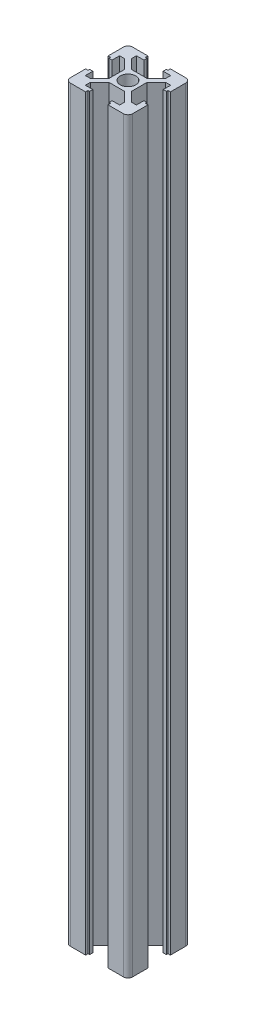
SolidWorks part; units mm, degrees
ref_plane "前视基准面" through (0, 0, 0) normal (0, 0, 1) x (1, 0, 0)
ref_plane "上视基准面" through (0, 0, 0) normal (0, 1, 0) x (1, 0, 0)
ref_plane "右视基准面" through (0, 0, 0) normal (1, 0, 0) x (0, 0, -1)
other "Configuration Table"
sketch "草图1" plane through (0, 0, 0) normal (0, 1, 0) x (1, 0, 0)
  line L0 (-4.4156, 1.3346) -> (-4.4156, 4.4346) construction
  line L1 (-4.4156, 3.874) -> (-4.4156, -1.2047)
  line L2 (1.7237, 4.9346) -> (-3.3549, 4.9346)
  line L3 (2.7844, -1.2047) -> (2.7844, 3.874)
  line L4 (-3.3549, -2.2654) -> (1.7237, -2.2654)
  line L5 (-10.8156, 1.3346) -> (9.1844, 1.3346) construction
  line L6 (-0.8156, 11.3346) -> (-0.8156, -8.6654) construction
  line L7 (-10.8156, 11.3346) -> (-0.8156, 1.3346) construction
  line L8 (-10.8156, 4.9346) -> (-4.4156, 4.9346) construction
  line L9 (-10.0156, 4.4346) -> (-3.9156, 4.4346) construction
  line L10 (-9.0156, 6.8346) -> (-6.3156, 6.8346) construction
  line L11 (-7.3763, 6.8346) -> (-4.4156, 3.874) construction
  line L12 (-10.8156, 9.8346) -> (-10.8156, 4.9346)
  line L13 (-10.8156, 4.9346) -> (-10.0156, 4.9346)
  line L14 (-10.0156, 4.9346) -> (-10.0156, 4.4346)
  line L15 (-10.0156, 4.4346) -> (-9.0156, 4.4346)
  line L16 (-9.0156, 4.4346) -> (-9.0156, 6.8346)
  line L17 (-9.0156, 6.8346) -> (-7.3763, 6.8346)
  line L18 (-7.3763, 6.8346) -> (-4.4156, 3.874)
  line L19 (-3.9156, 10.5346) -> (-3.9156, 9.5346)
  line L20 (-4.4156, 10.5346) -> (-3.9156, 10.5346)
  line L21 (-4.4156, 11.3346) -> (-4.4156, 10.5346)
  line L22 (-9.3156, 11.3346) -> (-4.4156, 11.3346)
  line L23 (-3.9156, 9.5346) -> (-6.3156, 9.5346)
  line L24 (-6.3156, 9.5346) -> (-6.3156, 7.8953)
  line L25 (-6.3156, 7.8953) -> (-3.3549, 4.9346)
  line L26 (9.1844, 11.3346) -> (-0.8156, 1.3346) construction
  line L27 (4.6844, 7.8953) -> (1.7237, 4.9346)
  line L28 (4.6844, 9.5346) -> (4.6844, 7.8953)
  line L29 (2.2844, 9.5346) -> (4.6844, 9.5346)
  line L30 (2.2844, 10.5346) -> (2.2844, 9.5346)
  line L31 (2.7844, 10.5346) -> (2.2844, 10.5346)
  line L32 (2.7844, 11.3346) -> (2.7844, 10.5346)
  line L33 (7.6844, 11.3346) -> (2.7844, 11.3346)
  line L34 (9.1844, 9.8346) -> (9.1844, 4.9346)
  line L35 (9.1844, 4.9346) -> (8.3844, 4.9346)
  line L36 (8.3844, 4.9346) -> (8.3844, 4.4346)
  line L37 (8.3844, 4.4346) -> (7.3844, 4.4346)
  line L38 (7.3844, 4.4346) -> (7.3844, 6.8346)
  line L39 (7.3844, 6.8346) -> (5.7451, 6.8346)
  line L40 (5.7451, 6.8346) -> (2.7844, 3.874)
  line L41 (9.1844, -8.6654) -> (-0.8156, 1.3346) construction
  line L42 (5.7451, -4.1654) -> (2.7844, -1.2047)
  line L43 (7.3844, -4.1654) -> (5.7451, -4.1654)
  line L44 (7.3844, -1.7654) -> (7.3844, -4.1654)
  line L45 (8.3844, -1.7654) -> (7.3844, -1.7654)
  line L46 (8.3844, -2.2654) -> (8.3844, -1.7654)
  line L47 (9.1844, -2.2654) -> (8.3844, -2.2654)
  line L48 (9.1844, -7.1654) -> (9.1844, -2.2654)
  line L49 (7.6844, -8.6654) -> (2.7844, -8.6654)
  line L50 (2.7844, -8.6654) -> (2.7844, -7.8654)
  line L51 (2.7844, -7.8654) -> (2.2844, -7.8654)
  line L52 (2.2844, -7.8654) -> (2.2844, -6.8654)
  line L53 (2.2844, -6.8654) -> (4.6844, -6.8654)
  line L54 (4.6844, -6.8654) -> (4.6844, -5.226)
  line L55 (4.6844, -5.226) -> (1.7237, -2.2654)
  line L56 (-10.8156, -8.6654) -> (-0.8156, 1.3346) construction
  line L57 (-6.3156, -5.226) -> (-3.3549, -2.2654)
  line L58 (-6.3156, -6.8654) -> (-6.3156, -5.226)
  line L59 (-3.9156, -6.8654) -> (-6.3156, -6.8654)
  line L60 (-3.9156, -7.8654) -> (-3.9156, -6.8654)
  line L61 (-4.4156, -7.8654) -> (-3.9156, -7.8654)
  line L62 (-4.4156, -8.6654) -> (-4.4156, -7.8654)
  line L63 (-9.3156, -8.6654) -> (-4.4156, -8.6654)
  line L64 (-10.8156, -7.1654) -> (-10.8156, -2.2654)
  line L65 (-10.8156, -2.2654) -> (-10.0156, -2.2654)
  line L66 (-10.0156, -2.2654) -> (-10.0156, -1.7654)
  line L67 (-10.0156, -1.7654) -> (-9.0156, -1.7654)
  line L68 (-9.0156, -1.7654) -> (-9.0156, -4.1654)
  line L69 (-9.0156, -4.1654) -> (-7.3763, -4.1654)
  line L70 (-7.3763, -4.1654) -> (-4.4156, -1.2047)
  arc A0 (-10.8156, 9.8346) -> (-9.3156, 11.3346) centre (-9.3156, 9.8346) cw
  circle A1 centre (-0.8156, 1.3346) radius 2.5
  arc A2 (7.6844, 11.3346) -> (9.1844, 9.8346) centre (7.6844, 9.8346) cw
  arc A3 (9.1844, -7.1654) -> (7.6844, -8.6654) centre (7.6844, -7.1654) cw
  arc A4 (-9.3156, -8.6654) -> (-10.8156, -7.1654) centre (-9.3156, -7.1654) cw
  point P13 (-0.8156, 1.3346)
  point P84 (-0.8156, 1.3346)
  dimension "D8" = 1.5
  dimension "D9" = 5
  dimension "D1" = 20
  dimension "D2" = 6.2
  dimension "D3" = 7.2
  dimension "D4" = 11
  dimension "D5" = 1.5
  dimension "D6" = 0.8
  dimension "D7" = 1.8
  dimension "D10" = 7.2
extrude "凸台-拉伸1" add sketch "草图1" along normal blind 240
